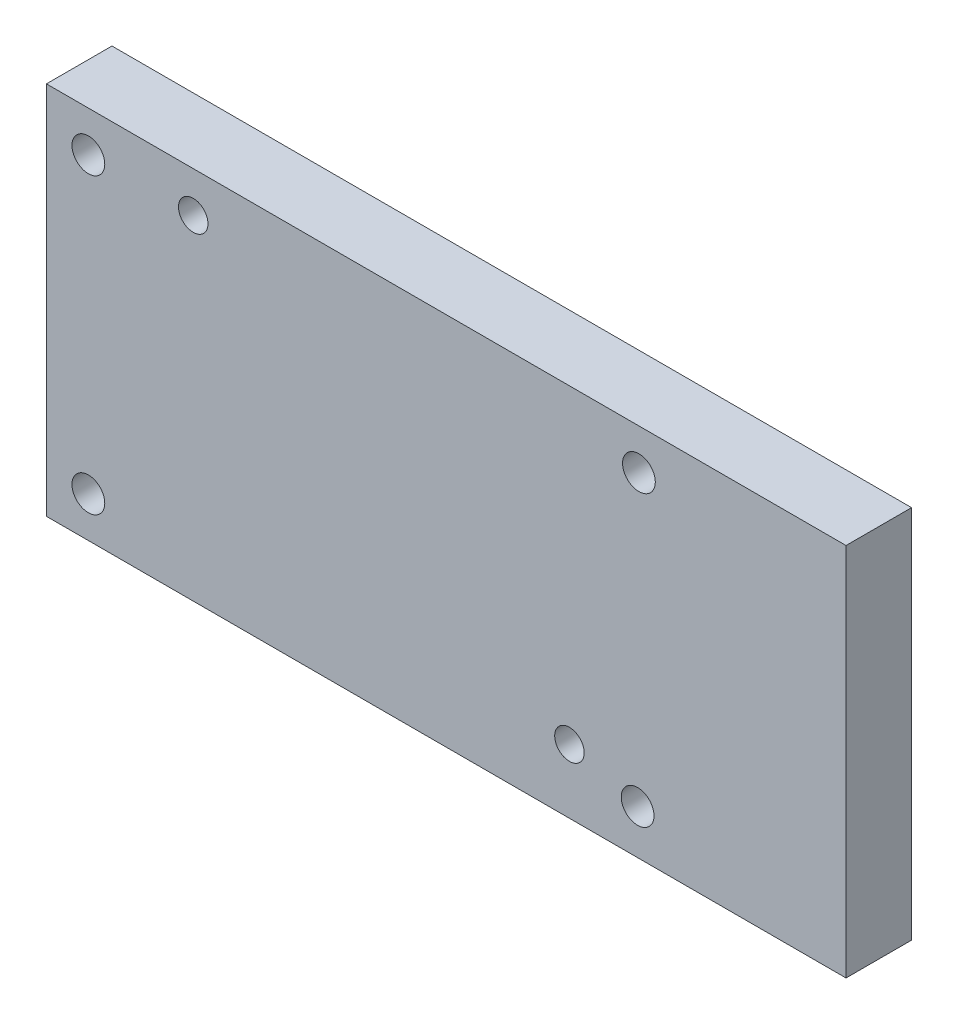
SolidWorks part; units mm, degrees
ref_plane "Front Plane" through (0, 0, 0) normal (0, 0, 1) x (1, 0, 0)
ref_plane "Top Plane" through (0, 0, 0) normal (0, 1, 0) x (1, 0, 0)
ref_plane "Right Plane" through (0, 0, 0) normal (1, 0, 0) x (0, 0, -1)
sketch "Sketch1" plane through (0, 0, 0) normal (0, 0, 1) x (1, 0, 0)
  line L0 (-61, 14.2875) -> (-49.1195, 14.2875) construction
  line L1 (0, 0) -> (-61, 0)
  line L2 (0, 0) -> (0, 28.575)
  line L3 (0, 28.575) -> (-61, 28.575)
  line L4 (-61, 0) -> (-61, 28.575)
  circle A0 centre (-57.8, 3.0875) radius 1.25
  circle A1 centre (-57.8, 25.4875) radius 1.25
  circle A2 centre (-15.8, 25.4875) radius 1.25
  circle A3 centre (-15.9, 3.3875) radius 1.25
  circle A4 centre (-49.8, 25.4875) radius 1.125
  circle A5 centre (-21.1, 4.8875) radius 1.125
  dimension "D3" = 2.5
  dimension "D5" = 22.4
  dimension "D6" = 41.9
  dimension "D7" = 42
  dimension "D8" = 3.2
  dimension "D9" = 2.25
  dimension "D11" = 36.7
  dimension "D1" = 61
  dimension "D2" = 28.575
  dimension "D4" = 0.3
  dimension "D10" = 8
  dimension "D12" = 1.8
extrude "Boss-Extrude1" add sketch "Sketch1" along normal blind 5
